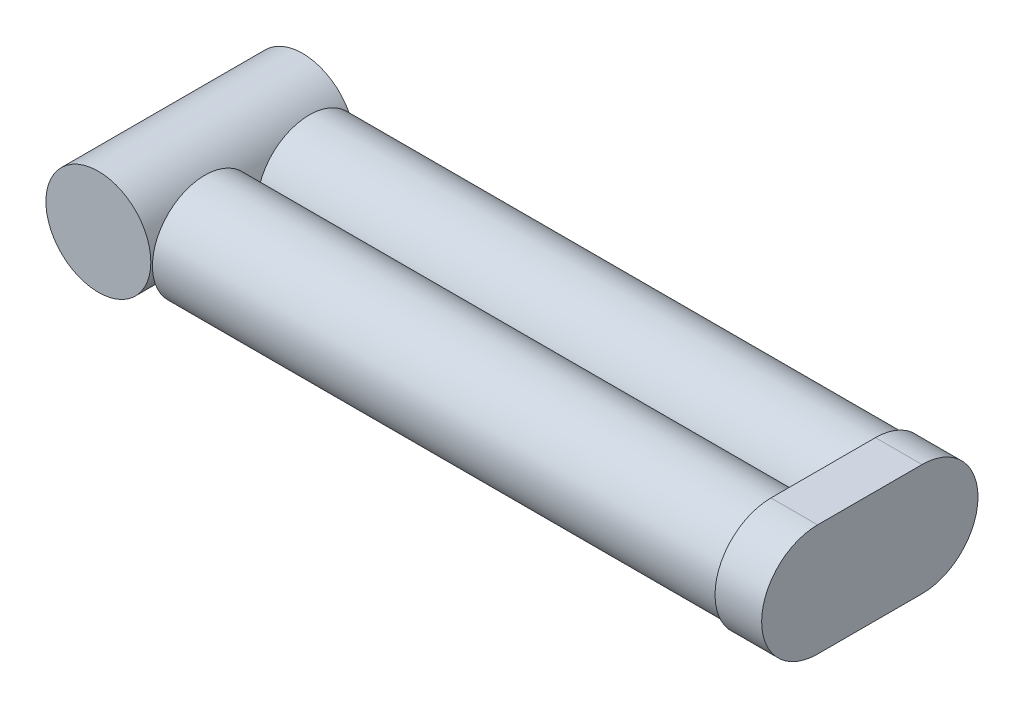
SolidWorks part; units mm, degrees
ref_plane "Front Plane" through (0, 0, 0) normal (0, 0, 1) x (1, 0, 0)
ref_plane "Top Plane" through (0, 0, 0) normal (0, 1, 0) x (1, 0, 0)
ref_plane "Right Plane" through (0, 0, 0) normal (1, 0, 0) x (0, 0, -1)
sketch "Sketch1" plane through (0, 0, 0) normal (1, 0, 0) x (0, 0, -1)
  line L0 (0, 55) -> (0, -55) construction
  circle A0 centre (-11.2, 0) radius 11.25
  circle A1 centre (11.2, 0) radius 11.25
  point P8 (22.45, 0)
  point P9 (-22.45, 0)
  dimension "D1" = 22.5
  dimension "D2" = 44.9
extrude "Boss-Extrude1" add sketch "Sketch1" along normal blind 131.4 contours A0 | A1 | A1 A0
sketch "Sketch2" plane through (131.4, 0, 0) normal (1, 0, 0) x (0, 0, -1)
  line L0 (11.2, 0) -> (-11.2, 0) construction
  line L1 (11.2, -12) -> (-11.2, -12)
  line L2 (11.2, 12) -> (-11.2, 12)
  arc A0 (11.2, -12) -> (11.2, 12) centre (11.2, 0) ccw
  arc A1 (-11.2, 12) -> (-11.2, -12) centre (-11.2, 0) ccw
  point P4 (0, 0)
  dimension "D1" = 24
extrude "Boss-Extrude5" add sketch "Sketch2" against normal blind 1
sketch "Sketch3" plane through (130.4, 0, 0) normal (-1, 0, 0) x (0, 0, 1)
  line L0 (-11.2, -11) -> (11.2, -11)
  line L1 (11.2, 11) -> (-11.2, 11)
  line L2 (-11.2, -12) -> (11.2, -12)
  line L3 (11.2, 12) -> (-11.2, 12)
  line L4 (-11.2, -12) -> (11.2, -12)
  line L5 (11.2, 12) -> (-11.2, 12)
  arc A0 (-11.2, 11) -> (-11.2, -11) centre (-11.2, 0) ccw
  arc A1 (11.2, -11) -> (11.2, 11) centre (11.2, 0) ccw
  arc A2 (-11.2, 12) -> (-11.2, -12) centre (-11.2, 0) ccw
  arc A3 (11.2, -12) -> (11.2, 12) centre (11.2, 0) ccw
  arc A4 (-11.2, 12) -> (-11.2, -12) centre (-11.2, 0) ccw
  arc A5 (11.2, -12) -> (11.2, 12) centre (11.2, 0) ccw
  dimension "D1" = 0
  dimension "D2" = 1
extrude "Boss-Extrude6" add sketch "Sketch3" along normal offset from surface (9 mm away) 10 up to face at (131.4, 0, 0)
sketch "Sketch4" plane through (0, 0, 0) normal (0, 0, 1) x (1, 0, 0)
  line L0 (131.4, -12) -> (131.4, 12) construction
  circle A0 centre (-12.15, 0) radius 11.25
  point P2 (-23.4, 0)
  point P5 (0, 0)
  dimension "D1" = 22.5
  dimension "D2" = 154.8
extrude "Boss-Extrude7" add sketch "Sketch4" along normal mid plane 43.8 separate body
